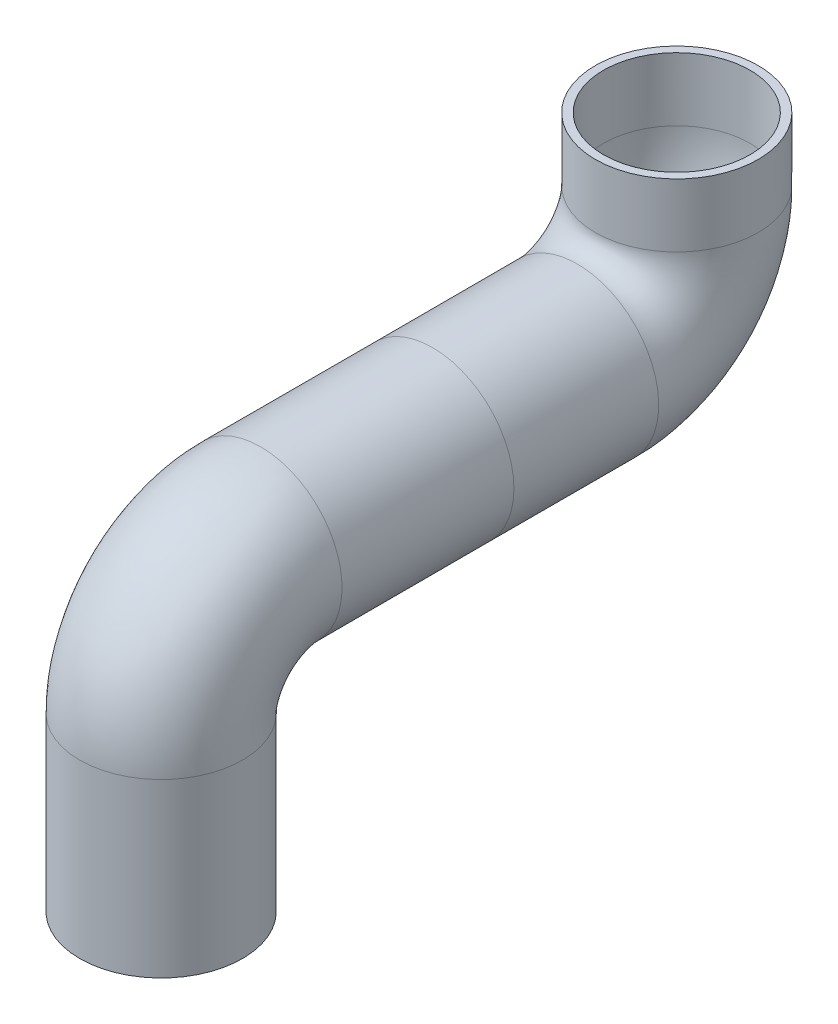
SolidWorks part; units mm, degrees
ref_plane "Front Plane" through (0, 0, 0) normal (0, 0, 1) x (1, 0, 0)
ref_plane "Top Plane" through (0, 0, 0) normal (0, 1, 0) x (1, 0, 0)
ref_plane "Right Plane" through (0, 0, 0) normal (1, 0, 0) x (0, 0, -1)
sketch "Sketch1" plane through (0, 0, 0) normal (1, 0, 0) x (0, 0, -1)
  line L0 (0, 0) -> (0, 316.67)
  line L1 (183.33, 500) -> (500, 500)
  line L2 (500, 500) -> (766.67, 500)
  line L3 (950, 683.33) -> (950, 800)
  arc A0 (0, 316.67) -> (183.33, 500) centre (183.33, 316.67) cw
  arc A1 (766.67, 500) -> (950, 683.33) centre (766.67, 683.33) ccw
  point P6 (0, 500)
  point P11 (950, 500)
  dimension "D3" = 183.33
  dimension "D6" = 183.33
  dimension "D1" = 500
  dimension "D2" = 500
  dimension "D4" = 450
  dimension "D5" = 300
sketch "Sketch2" plane through (0, 0, 0) normal (0, 1, 0) x (1, 0, 0)
  circle A0 centre (0, 0) radius 135
  circle A1 centre (0, 0) radius 150
  dimension "D1" = 270
  dimension "D2" = 300
sweep "Sweep2" add profiles "Sketch2" path "Sketch1"
